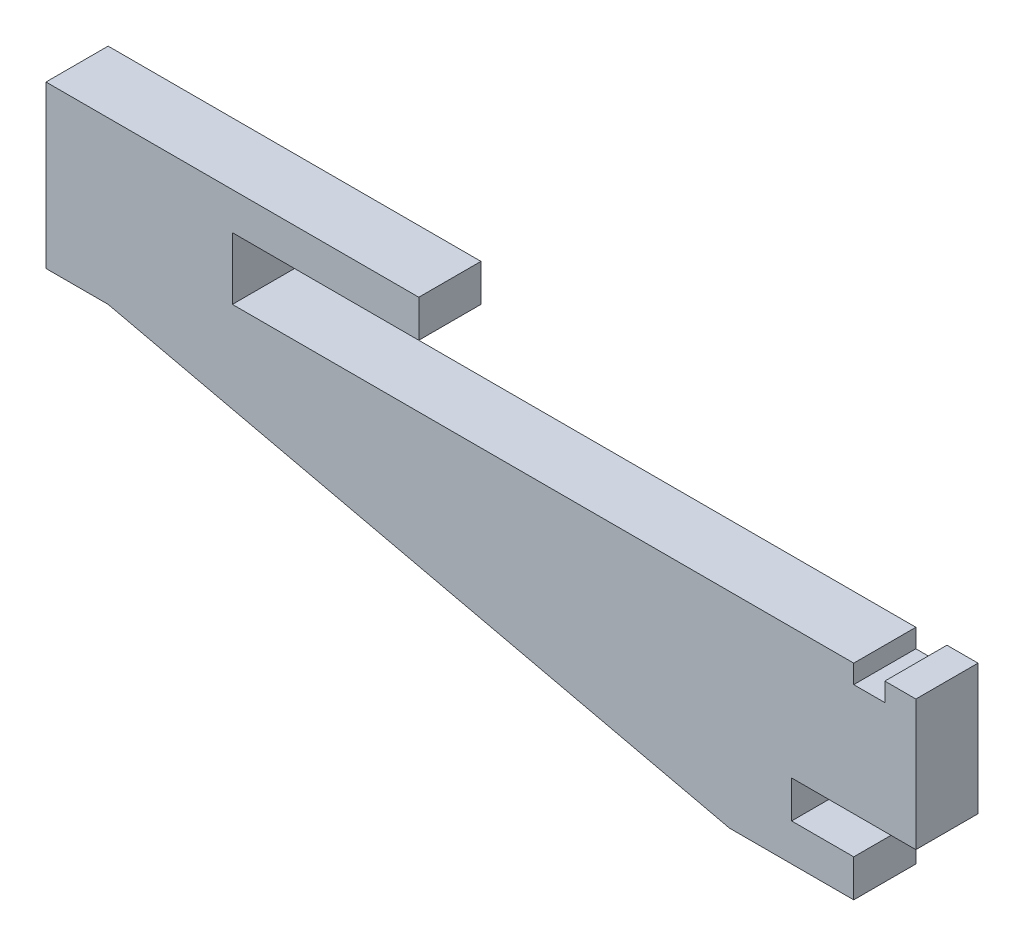
SolidWorks part; units mm, degrees
ref_plane "Front Plane" through (0, 0, 0) normal (0, 0, 1) x (1, 0, 0)
ref_plane "Top Plane" through (0, 0, 0) normal (0, 1, 0) x (1, 0, 0)
ref_plane "Right Plane" through (0, 0, 0) normal (1, 0, 0) x (0, 0, -1)
sketch "Sketch1" plane through (0, 0, 0) normal (0, 0, 1) x (1, 0, 0)
  line L0 (-70, -139.5) -> (0, -139.5)
  line L1 (0, -139.5) -> (0, -150)
  line L2 (0, -150) -> (-10, -150)
  line L3 (-10, -150) -> (-10, -153)
  line L4 (-10, -153) -> (-5, -153)
  line L5 (-10, -153) -> (-1, -153) construction
  line L6 (-5, -153) -> (-5, -156)
  line L7 (-5, -156) -> (-15, -156)
  line L8 (-15, -156) -> (-65, -144.5)
  line L9 (-65, -144.5) -> (-70, -144.5)
  line L10 (-70, -144.5) -> (-70, -139.5)
  dimension "D1" = 5
  dimension "D2" = 5
  dimension "D3" = 5
  dimension "D4" = 3
  dimension "D5" = 10
ref_plane "Plane1" through (0, 0, -2.5) normal (0, 0, 1) x (1, 0, 0)
sketch "Sketch2" plane through (0, 0, -2.5) normal (0, 0, 1) x (1, 0, 0)
  line L0 (-70, -139.5) -> (-70, -131.5)
  line L1 (-70, -131.5) -> (-40, -131.5)
  line L2 (-40, -131.5) -> (-40, -134.5)
  line L3 (-70, -134.5) -> (0, -134.5) construction
  line L4 (-40, -134.5) -> (-55, -134.5)
  line L5 (-55, -134.5) -> (-55, -139.5)
  line L10 (-70, -144.5) -> (-65, -144.5)
  line L11 (-70, -139.5) -> (-70, -144.5)
  line L12 (0, -139.5) -> (-70, -139.5)
  line L13 (0, -150) -> (0, -139.5)
  line L14 (-10, -150) -> (0, -150)
  line L15 (-10, -153) -> (-10, -150)
  line L16 (-5, -153) -> (-10, -153)
  line L17 (-5, -156) -> (-5, -153)
  line L18 (-15, -156) -> (-5, -156)
  line L19 (-65, -144.5) -> (-15, -156)
  line L20 (-70, -144.5) -> (-65, -144.5)
  line L21 (-70, -139.5) -> (-70, -144.5)
  line L22 (0, -139.5) -> (-55, -139.5)
  line L23 (0, -150) -> (0, -139.5)
  line L24 (-10, -150) -> (0, -150)
  line L25 (-10, -153) -> (-10, -150)
  line L26 (-5, -153) -> (-10, -153)
  line L27 (-5, -156) -> (-5, -153)
  line L28 (-15, -156) -> (-5, -156)
  line L29 (-65, -144.5) -> (-15, -156)
  dimension "D2" = 13
  dimension "D3" = 30
  dimension "D4" = 15
  dimension "D1" = 0
extrude "Boss-Extrude1" add sketch "Sketch2" against normal blind 5
sketch "Sketch3" plane through (0, 0, -7.5) normal (0, 0, -1) x (-1, 0, 0)
  line L0 (5, -139.5) -> (2.5, -139.5) construction
  line L1 (5, -139.5) -> (2.5, -139.5)
  line L2 (2.5, -139.5) -> (2.5, -141)
  line L3 (2.5, -141) -> (5, -141)
  line L4 (5, -141) -> (5, -139.5)
  dimension "D1" = 1.5
extrude "Cut-Extrude1" cut sketch "Sketch3" against normal through all
